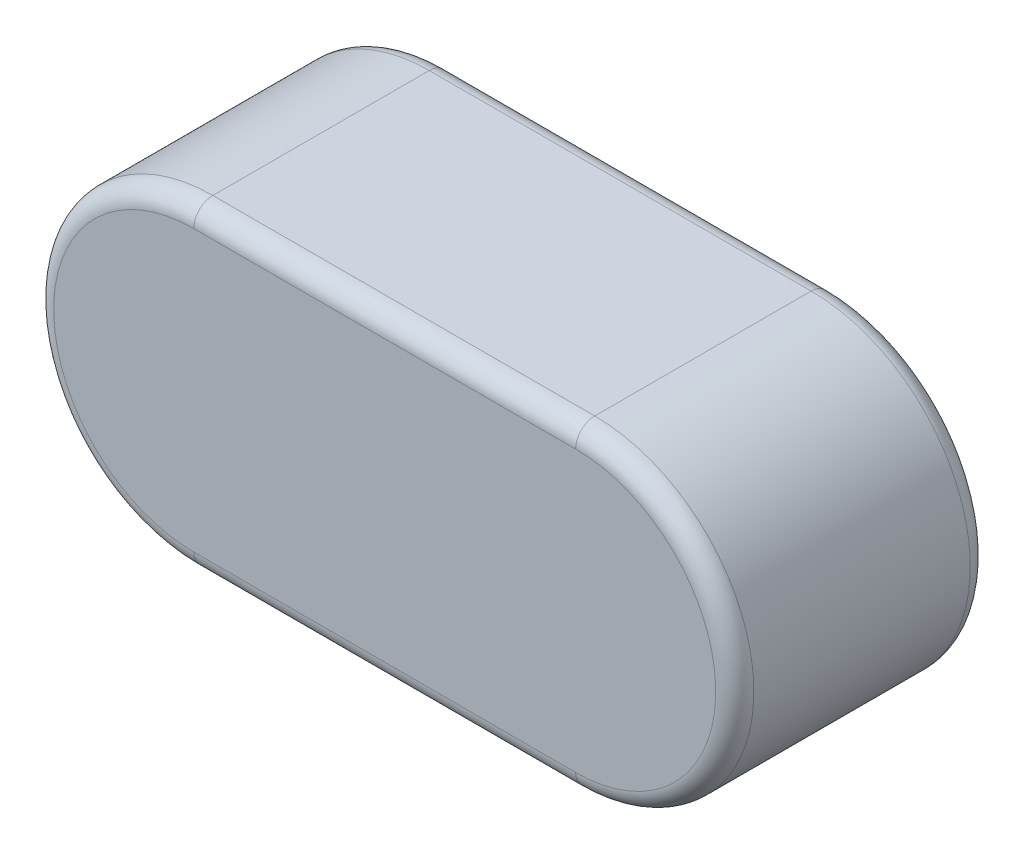
SolidWorks part; units mm, degrees
material "45"
ref_plane "基准面1" through (0, 0, 0) normal (0, 0, 1) x (1, 0, 0)
ref_plane "基准面2" through (0, 0, 0) normal (0, 1, 0) x (1, 0, 0)
ref_plane "基准面3" through (0, 0, 0) normal (1, 0, 0) x (0, 0, -1)
sketch "尺寸草图" plane through (0, 0, 0) normal (0, 0, 1) x (1, 0, 0)
  line L0 (-11, 0) -> (11, 0) construction
  point P3 (-8, 0)
  point P4 (-0.6, 0)
  point P5 (0, 0)
  point P8 (-10, 0)
  point P11 (0, 0)
  dimension "L" = 22
  dimension "b" = 10
  dimension "h" = 8
  dimension "C" = 0.6
  dimension "r" = 0.6
sketch "草图1" plane through (0, 0, 0) normal (0, 0, 1) x (1, 0, 0)
  line L0 (-28.0599, 0) -> (30.562, 0) construction
  line L1 (-6, 5) -> (6, 5)
  line L2 (-6, -5) -> (6, -5)
  line L3 (0, 2.9108) -> (0, -2.1805) construction
  arc A0 (-6, 5) -> (-6, -5) centre (-6, 0) ccw
  arc A1 (6, 5) -> (6, -5) centre (6, 0) cw
  dimension "D3" = 22
  dimension "D1" = 5
extrude "基体-拉伸" add sketch "草图1" along normal blind 8
fillet "圆角1" radius 0.6 8 edges at (11, 0, 8) (0, 5, 8) (-11, 0, 8) (0, 5, 0) (11, 0, 0) (0, -5, 0) (-11, 0, 0) (0, -5, 8)
equation "\"D3@草图1\" = \"L@尺寸草图\""
equation "\"D1@草图1\" = \"b@尺寸草图\" / 2"
equation "\"D1@圆角1\" = \"r@尺寸草图\""
equation "\"D1@基体-拉伸\" = \"h@尺寸草图\""
